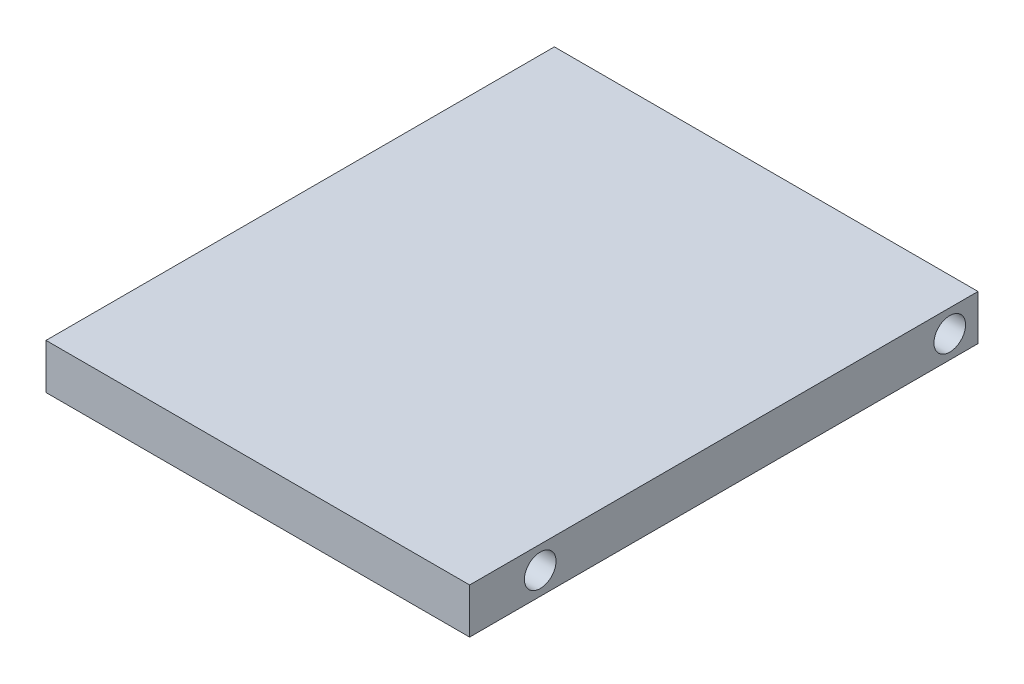
SolidWorks part; units mm, degrees
ref_plane "Front Plane" through (0, 0, 0) normal (0, 0, 1) x (1, 0, 0)
ref_plane "Top Plane" through (0, 0, 0) normal (0, 1, 0) x (1, 0, 0)
ref_plane "Right Plane" through (0, 0, 0) normal (1, 0, 0) x (0, 0, -1)
sketch "Sketch1" plane through (0, 0, 0) normal (0, 1, 0) x (1, 0, 0)
  line L1 (-37.5, 45) -> (37.5, 45)
  line L2 (-37.5, 45) -> (-37.5, -45)
  line L3 (-37.5, -45) -> (37.5, -45)
  line L4 (37.5, 45) -> (37.5, -45)
  point P4 (0, 45)
  point P6 (-37.5, 0)
  dimension "D1" = 75
  dimension "D2" = 90
extrude "Boss-Extrude1" add sketch "Sketch1" along normal blind 8
ref_plane "Plane1" through (37.5, 0, 0) normal (1, 0, 0) x (0, 0, -1)
sketch "Sketch2" plane through (37.5, 0, 0) normal (1, 0, 0) x (0, 0, -1)
  line L0 (45, 8) -> (45, 0) construction
  line L1 (45, 8) -> (45, 0) construction
  line L2 (-45, 8) -> (-45, 0) construction
  circle A0 centre (40, 4) radius 2.8
  circle A1 centre (-32.5, 4) radius 2.8
  point P4 (45, 4)
  dimension "D1" = 5.6
  dimension "D3" = 12.5
  dimension "D2" = 5
extrude "Cut-Extrude1" cut sketch "Sketch2" against normal blind 4.9
mirror "Mirror1" about plane through (0, 0, 0) normal (1, 0, 0) of "Cut-Extrude1"
